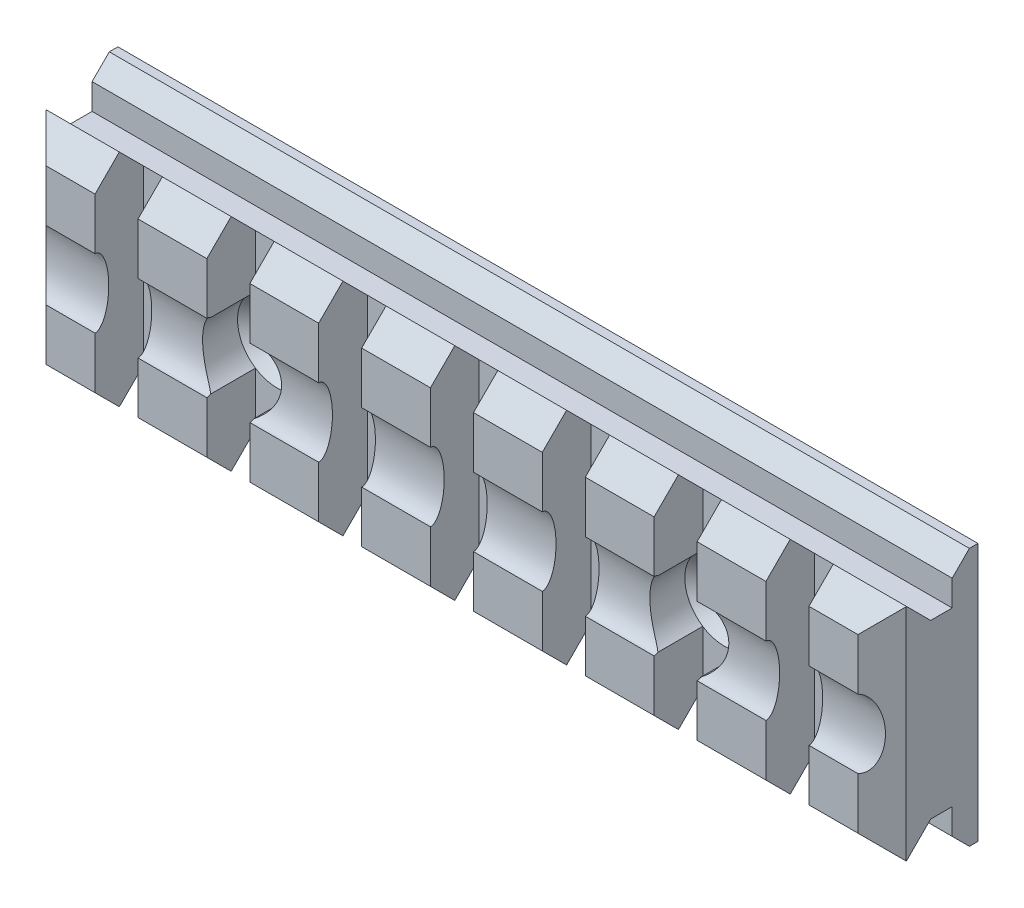
SolidWorks part; units mm, degrees
ref_plane "Ebene vorne" through (0, 0, 0) normal (0, 0, 1) x (1, 0, 0)
ref_plane "Ebene oben" through (0, 0, 0) normal (0, 1, 0) x (1, 0, 0)
ref_plane "Ebene rechts" through (0, 0, 0) normal (1, 0, 0) x (0, 0, -1)
sketch "Skizze1" plane through (0, 0, 0) normal (0, 0, 1) x (1, 0, 0)
  line L1 (-38.5927, 21.3922) -> (61.4073, 21.3922)
  line L2 (-38.5927, 21.3922) -> (-38.5927, -8.6078)
  line L3 (-38.5927, -8.6078) -> (61.4073, -8.6078)
  line L4 (61.4073, 21.3922) -> (61.4073, -8.6078)
  dimension "D1" = 100
  dimension "D2" = 30
extrude "Aufsatz-Linear austragen1" add sketch "Skizze1" along normal blind 3
sketch "Skizze4" plane through (0, 0, 3) normal (0, 0, 1) x (1, 0, 0)
  line L0 (-38.5927, 21.3922) -> (-38.5927, -8.6078) construction
  line L1 (-38.5927, 16.3922) -> (61.4073, 16.3922)
  line L2 (-38.5927, 16.3922) -> (-38.5927, -3.6078)
  line L3 (-38.5927, -3.6078) -> (61.4073, -3.6078)
  line L4 (61.4073, 16.3922) -> (61.4073, -3.6078)
  line L5 (61.4073, -8.6078) -> (61.4073, 21.3922) construction
  line L6 (61.4073, 21.3922) -> (-38.5927, 21.3922) construction
  line L7 (-38.5927, -8.6078) -> (61.4073, -8.6078) construction
  dimension "D1" = 5
  dimension "D2" = 5
extrude "Aufsatz-Linear austragen2" add sketch "Skizze4" along normal blind 2.5
sketch "Skizze7" plane through (61.4073, 0, 0) normal (1, 0, 0) x (0, 0, -1)
  line L0 (-5.5, 16.3922) -> (-8.3284, 19.2206)
  line L1 (-8.3284, 19.2206) -> (-11.1569, 16.3922)
  line L2 (-11.1569, 16.3922) -> (-11.1569, -3.6078)
  line L3 (-11.1569, -3.6078) -> (-8.3284, -6.4363)
  line L4 (-8.3284, -6.4363) -> (-5.5, -3.6078)
  line L6 (-5.5, -3.6078) -> (-5.5, 16.3922) construction
  line L16 (0, -8.6078) -> (0, 21.3922)
  line L17 (0, 21.3922) -> (-3, 21.3922)
  line L18 (-3, 21.3922) -> (-3, 16.3922)
  line L19 (-3, 16.3922) -> (-5.5, 16.3922)
  line L20 (-5.5, 16.3922) -> (-5.5, -3.6078)
  line L21 (-5.5, -3.6078) -> (-3, -3.6078)
  line L22 (-3, -3.6078) -> (-3, -8.6078)
  line L23 (-3, -8.6078) -> (0, -8.6078)
  line L28 (-5.5, 16.3922) -> (-5.5, -3.6078)
  dimension "D1" = 135
  dimension "D2" = 4
  dimension "D3" = 0
extrude "Aufsatz-Linear austragen3" add sketch "Skizze7" against normal up to surface (100 mm away) up to face at (-38.5927, 7.0172, 3.1875)
chamfer "Fase1" distance 2.8 1 edges at (61.4073, 6.3922, 11.1569)
chamfer "Fase2" distance 2.8 1 edges at (-38.5927, 6.3922, 11.1569)
sketch "Skizze8" plane through (0, 0, 11.1569) normal (0, 0, 1) x (1, 0, 0)
  line L0 (-38.5927, 19.2206) -> (61.4073, 19.2206) construction
  line L1 (-30.0927, 19.2206) -> (-25.0927, 19.2206)
  line L2 (-30.0927, 19.2206) -> (-30.0927, -6.4363)
  line L3 (-30.0927, -6.4363) -> (-25.0927, -6.4363)
  line L4 (-25.0927, 19.2206) -> (-25.0927, -6.4363)
  line L5 (-38.5927, -6.4363) -> (61.4073, -6.4363) construction
  line L8 (-38.5927, -6.4078) -> (-38.5927, 19.1922) construction
  dimension "D1" = 5
  dimension "D2" = 8.5
extrude "Schnitt-Linear austragen1" cut sketch "Skizze8" against normal up to vertex (5.6569 mm away) up to point (-38.5927, -3.6079, 5.5)
pattern_linear "Lineares Muster1" count 7 spacing 13 along (1, 0, 0) of "Schnitt-Linear austragen1"
chamfer "Fase3" distance 2 angle 45 1 edges at (11.4073, 21.3922, 3)
chamfer "Fase4" distance 2 angle 45 1 edges at (11.4073, -8.6078, 3)
hole_wizard "Formsenkung für M4 Senkschraube mit Innensechskant1" positions "Skizze10" profile "Skizze9" countersink size "M4" standard "DIN"
sketch "Skizze10" plane through (0, 0, 5.5) normal (0, 0, 1) x (1, 0, 0)
  line L0 (-17.0927, 16.3922) -> (-17.0927, -3.6078) construction
  line L1 (-12.0927, 16.3922) -> (-17.0927, 16.3922) construction
  line L2 (39.9073, 16.3922) -> (34.9073, 16.3922) construction
  line L3 (39.9073, -3.6078) -> (39.9073, 16.3922) construction
  point P0 (-14.5927, 6.3922)
  point P2 (37.4073, 6.3922)
  dimension "D1" = 2.5
  dimension "D2" = 10
  dimension "D3" = 10
  dimension "D4" = 2.5
sketch "Skizze9" plane through (-14.5927, 6.3922, 5.5) normal (1, 0, 0) x (0, -1, 0)
  line L0 (0, 0) -> (0, 5.5)
  line L1 (0, 5.5) -> (2.25, 5.5)
  line L2 (2.25, 5.5) -> (2.25, 2.34)
  line L3 (2.25, 2.34) -> (4.59, 0)
  line L5 (4.59, 0) -> (0, 0)
  line L6 (-2.25, 2.34) -> (-4.59, 0) construction
  line L11 (0, -6.35) -> (0, 107.95) construction
  dimension "Bohrerdurchmesser" = 4.5
  dimension "Bohrungstiefe" = 5.5
  dimension "Senkdurchmesser (Oben)" = 9.18
  dimension "Senkwinkel (Oben)" = 90
ref_plane "Ebene1" through (61.4073, 0, 0) normal (1, 0, 0) x (0, 0, -1)
sketch "Skizze13" plane through (61.4073, 0, 0) normal (1, 0, 0) x (0, 0, -1)
  line L0 (-11.1569, -3.6078) -> (-11.1569, 16.3922) construction
  ellipse E0 centre (-11.1569, 6.3922) end of major axis (-11.1569, 10.3922) minor radius 1.6
extrude "Schnitt-Linear austragen2" cut sketch "Skizze13" against normal through all
sketch "Skizze14" plane through (0, 0, 5.5) normal (0, 0, 1) x (1, 0, 0)
  circle A0 centre (37.4073, 6.3922) radius 4.59
  circle A1 centre (-14.5927, 6.3922) radius 4.59
extrude "Schnitt-Linear austragen3" cut sketch "Skizze14" along normal up to surface (5.6569 mm away) up to face at (-8.0927, 13.3922, 11.1569)
